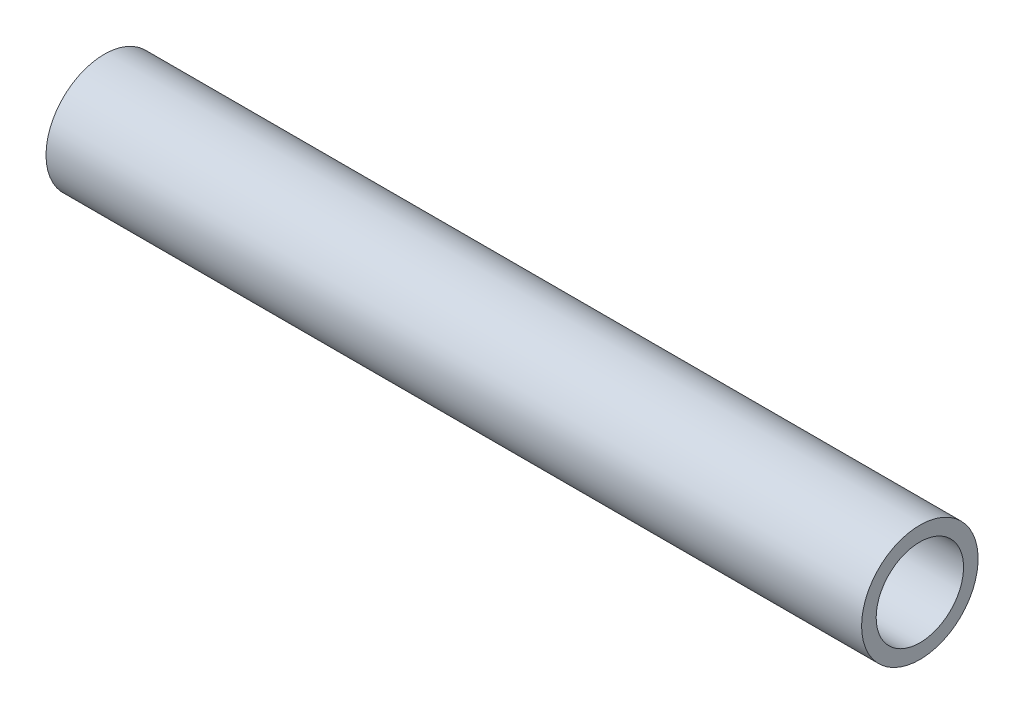
SolidWorks part; units mm, degrees
ref_plane "Front Plane" through (0, 0, 0) normal (0, 0, 1) x (1, 0, 0)
ref_plane "Top Plane" through (0, 0, 0) normal (0, 1, 0) x (1, 0, 0)
ref_plane "Right Plane" through (0, 0, 0) normal (1, 0, 0) x (0, 0, -1)
sketch "Sketch1" plane through (0, 0, 0) normal (0, 0, 1) x (1, 0, 0)
  line L0 (0, 0) -> (200, 0) construction
  line L1 (30, 7.5) -> (170, 7.5)
  line L6 (30, 10) -> (170, 10)
  line L7 (30, 10) -> (30, 7.5)
  line L9 (170, 10) -> (170, 7.5)
  dimension "L" = 200
  dimension "D_s" = 15
  dimension "D" = 20
revolve "Revolve1" add sketch "Sketch1" angle 360 about L0
